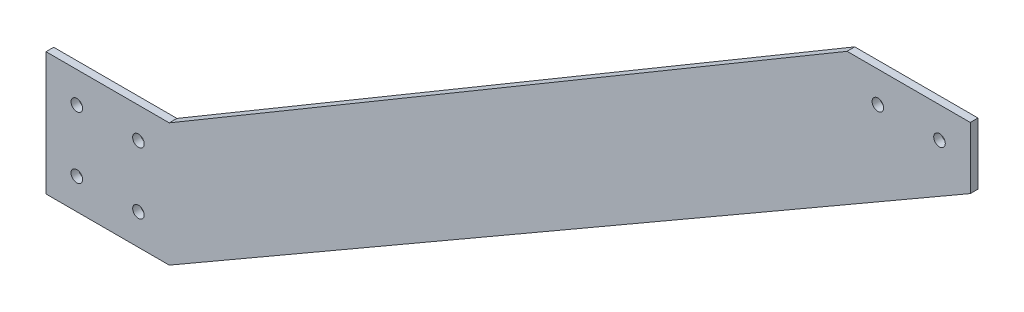
SolidWorks part; units mm, degrees
ref_plane "Front Plane" through (0, 0, 0) normal (0, 0, 1) x (1, 0, 0)
ref_plane "Top Plane" through (0, 0, 0) normal (0, 1, 0) x (1, 0, 0)
ref_plane "Right Plane" through (0, 0, 0) normal (1, 0, 0) x (0, 0, -1)
sketch "Sketch2" plane through (0, 0, 0) normal (0, 0, 1) x (1, 0, 0)
  line L1 (50.8, 0) -> (381, 190.6411)
  line L2 (381, 190.6411) -> (381, 216.0411)
  line L3 (381, 216.0411) -> (330.2, 216.0411)
  line L5 (0, 50.8) -> (0, 0)
  line L6 (50.8, 0) -> (0, 0)
  line L7 (0, 50.8) -> (50.8, 50.8)
  line L8 (50.8, 50.8) -> (330.2, 216.0411)
  dimension "D1" = 50.8
  dimension "D2" = 381
  dimension "D3" = 50.8
  dimension "D4" = 25.4
  dimension "D5" = 150
extrude "Boss-Extrude1" add sketch "Sketch2" along normal blind 3.175
sketch "Sketch3" plane through (0, 0, 3.175) normal (0, 0, 1) x (1, 0, 0)
  line L0 (25.4, 0) -> (0, 25.4) construction
  line L1 (0, 50.8) -> (0, 0) construction
  line L2 (381, 216.0411) -> (330.2, 216.0411) construction
  line L5 (381, 190.6411) -> (355.6, 216.0411) construction
  line L8 (0, 0) -> (50.8, 0) construction
  line L9 (12.7, 12.7) -> (38.1, 12.7) construction
  circle A0 centre (12.7, 12.7) radius 2.3813
  circle A1 centre (12.7, 38.1) radius 2.3812
  circle A2 centre (342.9, 203.3411) radius 2.3813
  circle A3 centre (368.3, 203.3411) radius 2.3813
  circle A4 centre (38.1, 12.7) radius 2.3812
  circle A5 centre (38.1, 38.1) radius 2.3812
  point P12 (12.7, 12.7)
  point P20 (368.3, 203.3411)
  point P23 (38.1, 12.7)
  dimension "D2" = 4.7625
  dimension "D4" = 4.7625
  dimension "D1" = 25.4
  dimension "D3" = 25.4
  dimension "D6" = 25.4
  dimension "D5" = 2
extrude "Cut-Extrude1" cut sketch "Sketch3" against normal through all
